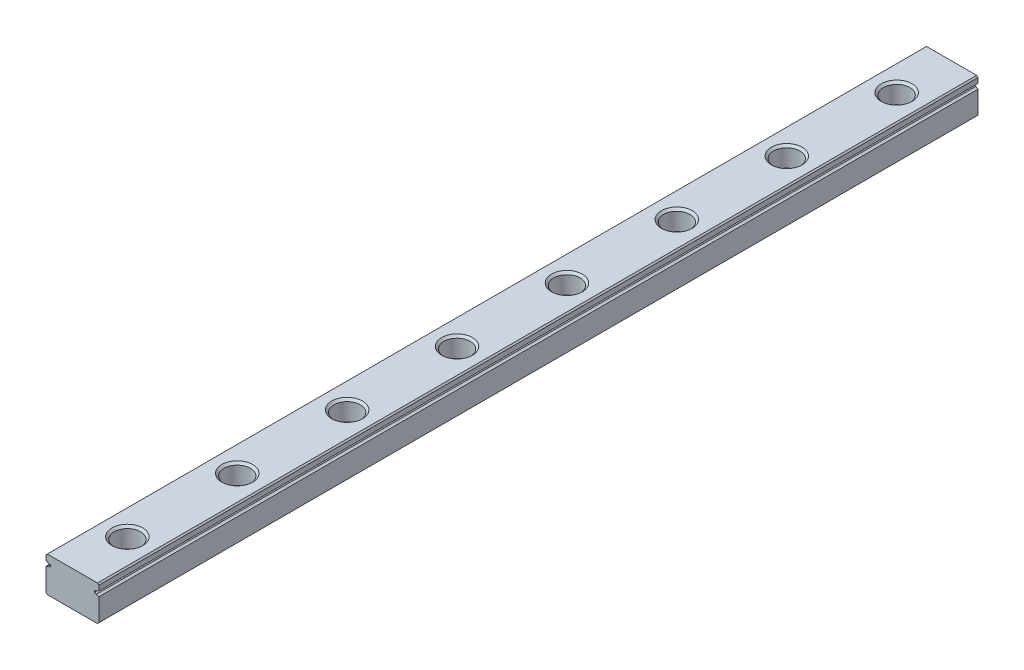
SolidWorks part; units mm, degrees
material "AISI 1045 鋼，冷拉"
ref_plane "Front Plane" through (0, 0, 0) normal (0, 0, 1) x (1, 0, 0)
ref_plane "Top Plane" through (0, 0, 0) normal (0, 1, 0) x (1, 0, 0)
ref_plane "Right Plane" through (0, 0, 0) normal (1, 0, 0) x (0, 0, -1)
sketch "Sketch1" plane through (0, 0, 0) normal (0, 0, 1) x (1, 0, 0)
  line L0 (-6, -4) -> (-6, 4) construction
  line L1 (-6, 4) -> (6, 4)
  line L2 (-6, -4) -> (6, -4)
  line L3 (-6, 4) -> (-6, 2.75)
  line L4 (-6, 2.75) -> (-5.5, 2.25) construction
  line L5 (-5.5, 2.25) -> (-5, 2.25)
  line L6 (-5.5, 1.75) -> (-6, 1.25) construction
  line L7 (-6, 1.25) -> (-6, -4)
  line L8 (-5, 2.25) -> (-5, 1.75)
  line L9 (-5, 1.75) -> (-5.5, 1.75)
  line L10 (-5.5, 1.75) -> (-5.25, 2) construction
  line L11 (-5.25, 2) -> (-5.5, 2.25) construction
  line L12 (-6, 2.75) -> (-6, 2.559)
  line L13 (-6, 1.25) -> (-6, 1.441)
  line L14 (0, 4) -> (0, -4) construction
  line L15 (5.25, 2) -> (5.5, 2.25) construction
  line L16 (5.5, 1.75) -> (5.25, 2) construction
  line L17 (5.5, 1.75) -> (6, 1.25) construction
  line L18 (6, 2.75) -> (5.5, 2.25) construction
  line L19 (6, -4) -> (6, 4) construction
  line L20 (6, 1.25) -> (6, 1.441)
  line L21 (6, 2.75) -> (6, 2.559)
  line L22 (5, 1.75) -> (5.5, 1.75)
  line L23 (5, 2.25) -> (5, 1.75)
  line L24 (6, 1.25) -> (6, -4)
  line L25 (5.5, 2.25) -> (5, 2.25)
  line L26 (6, 4) -> (6, 2.75)
  arc A0 (-6, 1.441) -> (-5.5, 1.75) centre (-6, 2) ccw
  arc A1 (-5.5, 2.25) -> (-6, 2.559) centre (-6, 2) ccw
  arc A2 (5.5, 2.25) -> (6, 2.559) centre (6, 2) cw
  arc A3 (6, 1.441) -> (5.5, 1.75) centre (6, 2) cw
  point P4 (-5, 2)
  point P28 (5, 2)
  dimension "D1" = 8
  dimension "D2" = 6
  dimension "D3" = 0.5
  dimension "D4" = 45
  dimension "D5" = 2
  dimension "D6" = 1
extrude "Boss-Extrude1" add sketch "Sketch1" along normal blind 200
chamfer "Chamfer1" distance 0.3 angle 45 4 edges at (-6, -4, 100) (6, -4, 100) (-6, 4, 100) (6, 4, 100)
hole_wizard "M3 六角承窩頭蓋螺釘的柱孔1" positions "3DSketch1" profile "Sketch3" counterbore size "M3" standard "ISO" end condition through all
sketch3d "3DSketch1"
  line L0 (0, 4, 0) -> (0, 4, 12.5) construction
  line L1 (5.7, 4, 0) -> (-5.7, 4, 0) construction
  point P0 (0, 4, 12.5)
  dimension "D1" = 12.5
sketch "Sketch3" plane through (0, 4, 12.5) normal (1, 0, 0) x (0, 0, 1)
  line L0 (0, 0) -> (0, 8)
  line L1 (1.75, 7.75) -> (2, 8)
  line L2 (3, 4.5) -> (1.75, 4.5)
  line L3 (1.75, 4.5) -> (1.75, 7.75)
  line L5 (3, 4.5) -> (3, 0.5)
  line L6 (3, 0.5) -> (3.5, 0)
  line L7 (3.5, 0) -> (0, 0)
  line L8 (-3, 0.5) -> (-3.5, 0) construction
  line L11 (0, -6.35) -> (0, 107.95) construction
  line L12 (2, 8) -> (0, 8)
  line L13 (-1.75, 7.75) -> (-2, 8) construction
  dimension "Thru Hole Dia." = 3.5
  dimension "Thru Hole Depth" = 8
  dimension "C'Bore Dia." = 6
  dimension "C'Bore Depth" = 4.5
  dimension "Near C'Sink Dia." = 7
  dimension "Near C'Sink Angle" = 90
  dimension "Far C'Sink Dia." = 4
  dimension "Far C'Sink Angle" = 90
pattern_linear "LPattern1" count 8 spacing 25 along (0, 0, 1) of "M3 六角承窩頭蓋螺釘的柱孔1"
